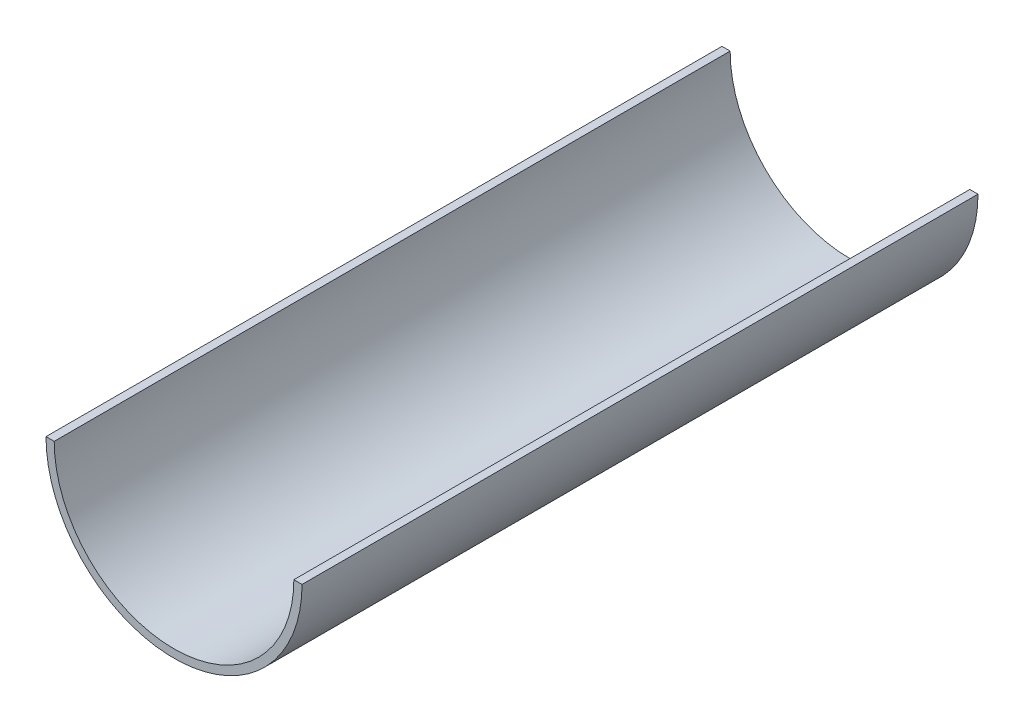
SolidWorks part; units mm, degrees
ref_plane "Front" through (0, 0, 0) normal (0, 0, 1) x (1, 0, 0)
ref_plane "Top" through (0, 0, 0) normal (0, 1, 0) x (1, 0, 0)
ref_plane "Right" through (0, 0, 0) normal (1, 0, 0) x (0, 0, -1)
sketch "Sketch1" plane through (0, 0, 0) normal (0, 0, 1) x (1, 0, 0)
  line L0 (-62.5, 0) -> (-58.5, 0)
  line L1 (58.5, 0) -> (62.5, 0)
  arc A0 (-62.5, 0) -> (62.5, 0) centre (0, 0) ccw
  arc A1 (-58.5, 0) -> (58.5, 0) centre (0, 0) ccw
  circle A2 centre (0, 0) radius 62.5 construction
  circle A3 centre (0, 0) radius 58.5 construction
  dimension "D1" = 125
  dimension "D2" = 4
extrude "Boss-Extrude1" add sketch "Sketch1" along normal blind 330
